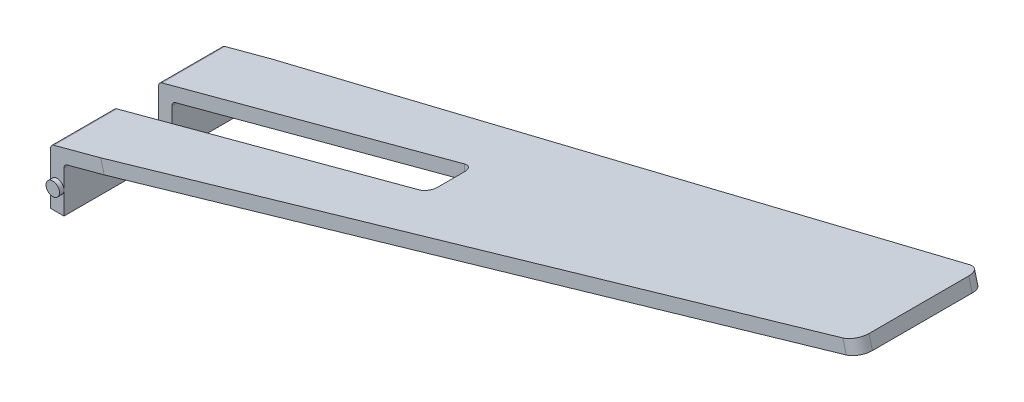
SolidWorks part; units mm, degrees
ref_plane "Front Plane" through (0, 0, 0) normal (0, 0, 1) x (1, 0, 0)
ref_plane "Top Plane" through (0, 0, 0) normal (0, 1, 0) x (1, 0, 0)
ref_plane "Right Plane" through (0, 0, 0) normal (1, 0, 0) x (0, 0, -1)
sketch "Sketch1" plane through (0, 0, 0) normal (0, 0, 1) x (1, 0, 0)
  line L0 (0, 0) -> (0, 1.2302)
  line L1 (0, 1.2302) -> (17.3867, 5.8889)
  line L2 (17.3867, 5.8889) -> (17.4643, 5.5992)
  line L3 (17.4643, 5.5992) -> (0.3, 1)
  line L4 (0.3, 1) -> (0.3, 0)
  line L5 (0.3, 0) -> (0, 0)
  dimension "D1" = 0.3
  dimension "D2" = 0.3
  dimension "D3" = 1
  dimension "D4" = 105
  dimension "D5" = 18
extrude "Boss-Extrude1" add sketch "Sketch1" along normal blind 3.8
chamfer "Chamfer1" distance 0.5 angle 88.3 2 edges at (17.4255, 5.7441, 3.8) (17.4255, 5.7441, 0)
sketch "Sketch3" plane through (0, 0, 3.8) normal (0, 0, 1) x (1, 0, 0)
  circle A0 centre (0.15, 0.5) radius 0.15
  dimension "D1" = 0.3
  dimension "D2" = 0.15
  dimension "D3" = 0.5
extrude "Boss-Extrude2" add sketch "Sketch3" along normal blind 0.1 and the other way blind 3.9
sketch "Sketch4" plane through (0, 0, 0) normal (0, -1, 0) x (1, 0, 0)
  line L0 (0, 3.8) -> (0, 0) construction
  line L1 (0, 2.4) -> (7, 2.4)
  line L2 (0, 2.4) -> (0, 1.4)
  line L3 (0, 1.4) -> (7, 1.4)
  line L4 (7, 2.4) -> (7, 1.4)
  line L5 (0, 0) -> (0.3, 0) construction
  point P6 (7, 1.9)
  dimension "D1" = 7
  dimension "D2" = 1
  dimension "D3" = 1.9
extrude "Cut-Extrude2" cut sketch "Sketch4" against normal blind 10
fillet "Fillet1" radius 0.1 4 edges at (0, 1.2302, 0.7) (0, 1.2302, 3.1) (0.3, 1, 0.7) (0.3, 1, 3.1)
fillet "Fillet2" radius 0.3 2 edges at (17.4255, 5.7441, 0.5) (17.4255, 5.7441, 3.3)
fillet "Fillet3" radius 0.2 2 edges at (7, 2.9506, 2.4) (7, 2.9506, 1.4)
